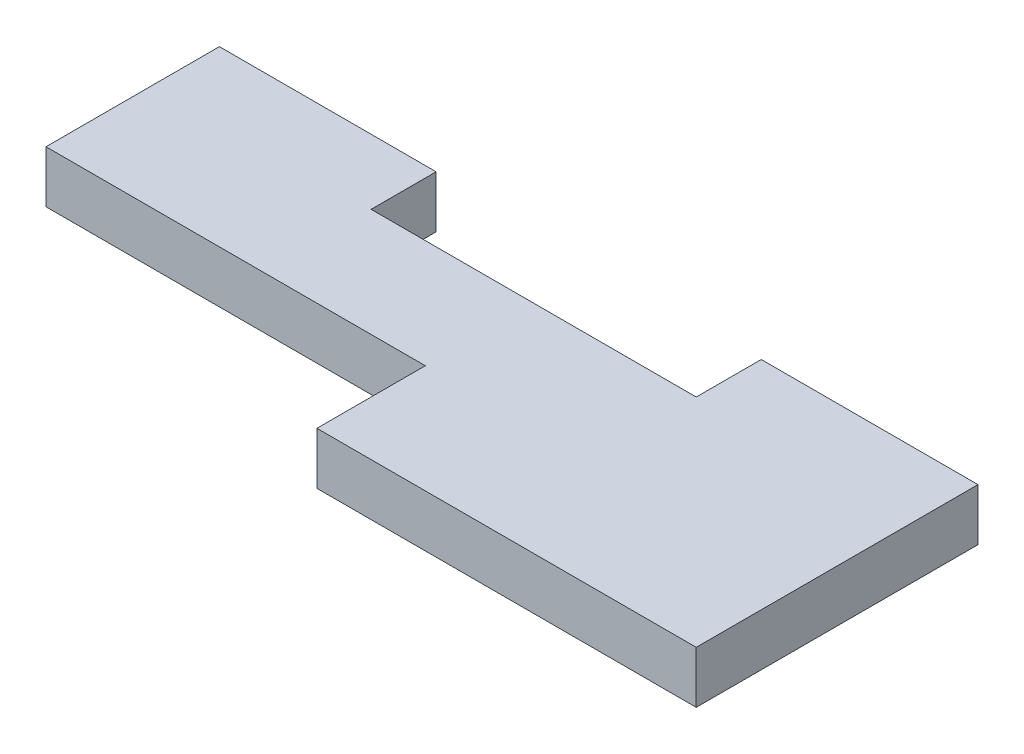
SolidWorks part; units mm, degrees
material "Epoxy, Unfilled"
ref_plane "Front Plane" through (0, 0, 0) normal (0, 0, 1) x (1, 0, 0)
ref_plane "Top Plane" through (0, 0, 0) normal (0, 1, 0) x (1, 0, 0)
ref_plane "Right Plane" through (0, 0, 0) normal (1, 0, 0) x (0, 0, -1)
sketch "Sketch1" plane through (0, 0, 0) normal (0, 1, 0) x (1, 0, 0)
  line L0 (0, 1.3) -> (1, 1.3)
  line L1 (1.75, 0) -> (3.5, 0)
  line L2 (0, 0.5) -> (0, 1.3)
  line L5 (1, 1.3) -> (1, 1)
  line L6 (1, 1) -> (2.5, 1)
  line L7 (2.5, 1) -> (2.5, 1.3)
  line L8 (2.5, 1.3) -> (3.5, 1.3)
  line L9 (3.5, 1.3) -> (3.5, 0)
  line L12 (1.75, 0) -> (1.75, 0.5)
  line L13 (1.75, 0.5) -> (0, 0.5)
  dimension "D1" = 1.5
  dimension "D2" = 1
  dimension "D3" = 0.3
  dimension "D4" = 1.3
  dimension "D5" = 0.5
extrude "Boss-Extrude1" add sketch "Sketch1" along normal blind 0.24
